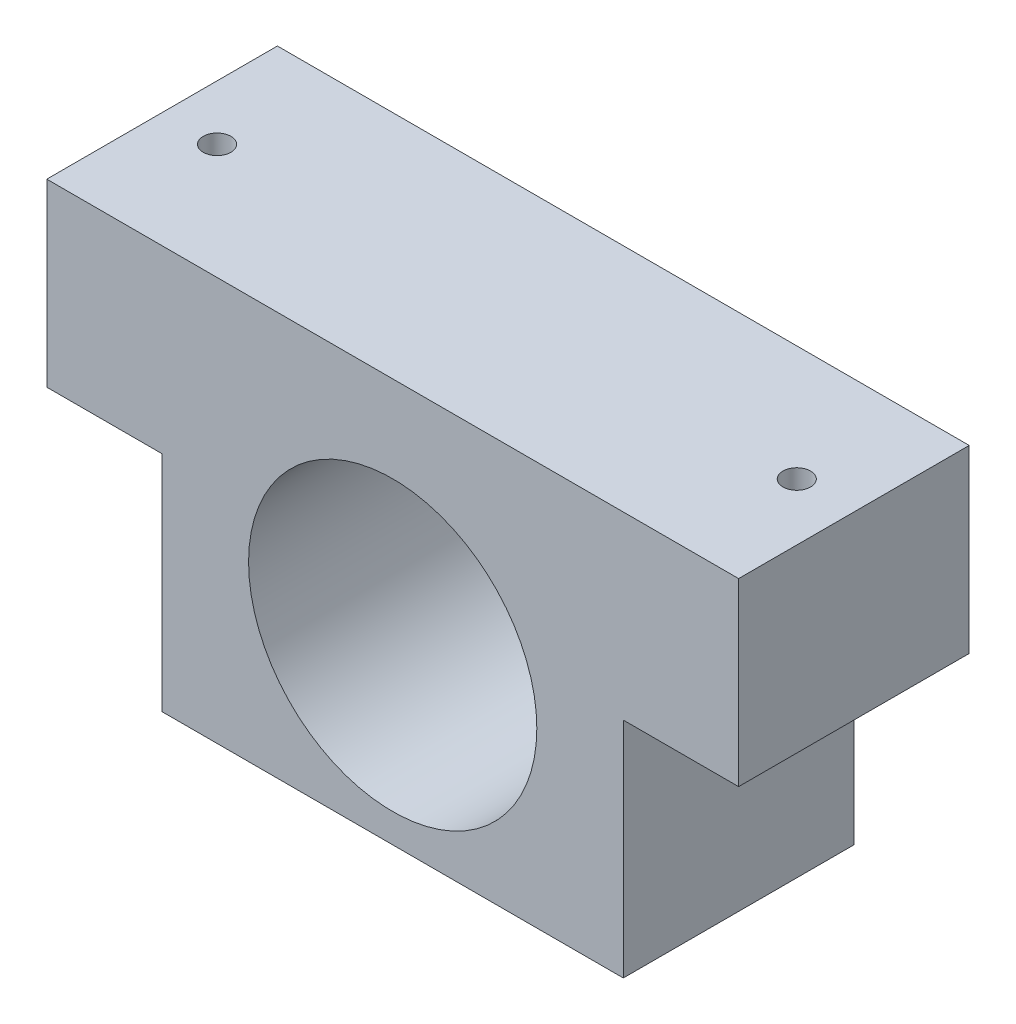
SolidWorks part; units mm, degrees
ref_plane "前视基准面" through (0, 0, 0) normal (0, 0, 1) x (1, 0, 0)
ref_plane "上视基准面" through (0, 0, 0) normal (0, 1, 0) x (1, 0, 0)
ref_plane "右视基准面" through (0, 0, 0) normal (1, 0, 0) x (0, 0, -1)
sketch "草图1" plane through (0, 0, 0) normal (0, 0, 1) x (1, 0, 0)
  line L0 (-290.6654, -145.6267) -> (-280.6654, -145.6267)
  line L1 (-340.6654, -130) -> (-280.6654, -130)
  line L2 (-340.6654, -130) -> (-340.6654, -145.6267)
  line L3 (-340.6654, -145.6267) -> (-330.6654, -145.6267)
  line L4 (-280.6654, -130) -> (-280.6654, -145.6267)
  line L5 (-295.6654, -130) -> (-325.6654, -130)
  line L6 (-290.6654, -145.6267) -> (-290.6654, -165)
  line L7 (-290.6654, -165) -> (-330.6654, -165)
  line L8 (-330.6654, -145.6267) -> (-330.6654, -165)
  circle A0 centre (-310.6654, -150) radius 12.5
  dimension "D5" = 25
  dimension "D1" = 60
  dimension "D2" = 40
  dimension "D3" = 10
  dimension "D4" = 35
  dimension "D6" = 20
extrude "凸台-拉伸1" add sketch "草图1" along normal blind 20 contours L3 L8 L7 L6 L0 L4 L1 L2 A0
hole_wizard "M2 六角头螺栓的柱形沉头孔1" positions "草图2" profile "草图4" counterbore size "M2" standard "GB" end condition through all
sketch "草图2" plane through (0, -145.6267, 0) normal (0, -1, 0) x (-1, 0, 0)
  point P0 (335.8973, -10)
  point P2 (285.6204, -10)
sketch "草图4" plane through (-335.8973, -145.6267, 10) normal (1, 0, 0) x (0, 0, -1)
  line L0 (0, 0) -> (0, 15.6267)
  line L1 (0, 15.6267) -> (1.2, 15.6267)
  line L3 (1.2, 15.6267) -> (1.2, 0.5)
  line L4 (1.2, 0.5) -> (3, 0.5)
  line L5 (3, 0.5) -> (3, 0)
  line L7 (3, 0) -> (0, 0)
  line L11 (0, -6.35) -> (0, 107.95) construction
  dimension "通孔孔直径" = 2.4
  dimension "通孔孔深度" = 15.6267
  dimension "柱形沉头孔直径" = 6
  dimension "柱形沉头孔深度" = 0.5
